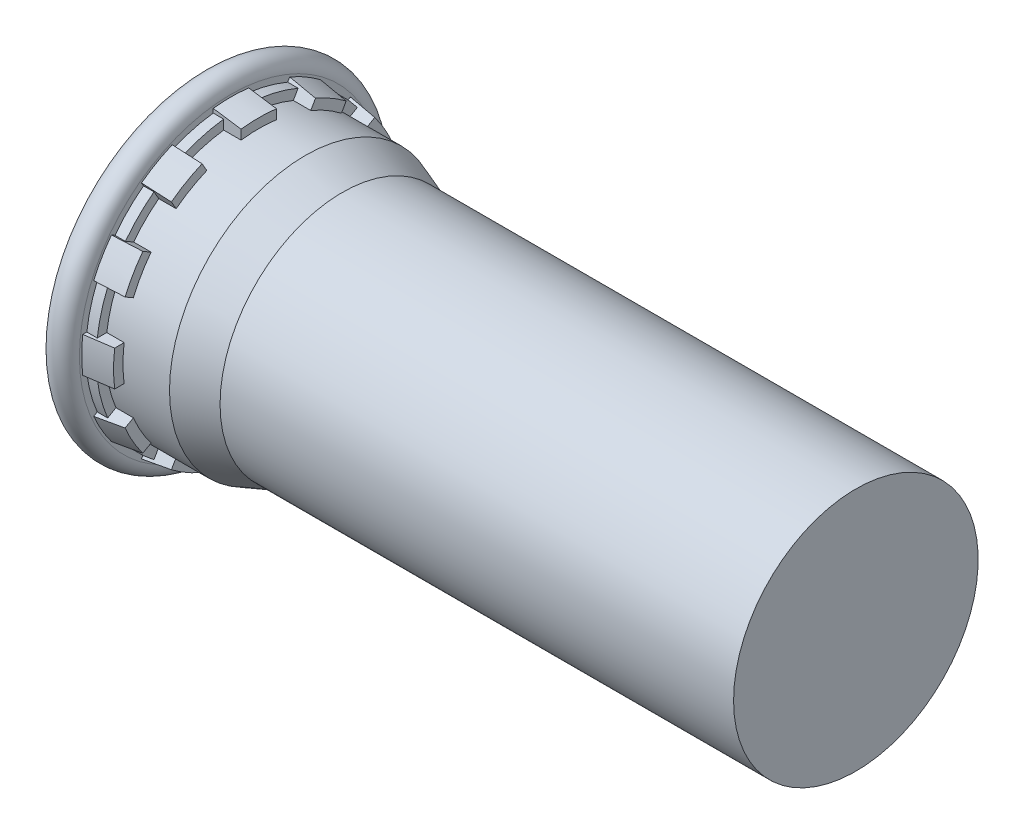
SolidWorks part; units mm, degrees
revolve "BaseBody" add sketch "BodySke" angle 360 about L6
sketch "BodySke" plane through (0, 0, 0) normal (0, 0, 1) x (1, 0, 0)
  line L0 (0, 0) -> (0, 4.4171)
  line L1 (0.8128, 4.4221) -> (0.8128, 4.3561)
  line L2 (0.8128, 4.3561) -> (1.6256, 4.238)
  line L3 (4.064, 3.5687) -> (19.05, 3.5687)
  line L4 (19.05, 3.5687) -> (19.05, 0)
  line L5 (19.05, 0) -> (0, 0)
  line L6 (0, 0) -> (50.554, 0) construction
  line L7 (1.6256, 4.238) -> (1.6256, 3.9624)
  line L8 (2.9823, 3.9624) -> (1.6256, 3.9624)
  line L9 (-9.525, 4.826) -> (9.525, 4.826) construction
  line L11 (4.064, 3.5687) -> (2.9823, 3.9624)
  line L13 (9.525, -4.826) -> (-9.525, -4.826) construction
  line L14 (0.0051, 4.4221) -> (0.0051, 4.4171)
  line L15 (0, 4.4171) -> (0.0051, 4.4171)
  arc A0 (0.0051, 4.4221) -> (0.8128, 4.4221) centre (0.4089, 4.4221) cw
  dimension "Length" = 19.05
  dimension "H_dia" = 9.652
  dimension "Shoulder_lower_dia" = 8.7122
  dimension "Shoulder_upper_dia" = 8.476
  dimension "D1" = 0.0051
  dimension "D2" = 0.0051
  dimension "Shoulder_ht" = 1.6256
  dimension "T_dim" = 0.8128
  dimension "Diameter" = 7.1374
  dimension "Neck_dia" = 7.9248
  dimension "Neck_len" = 4.064
  dimension "D3" = 20
cosmetic thread "ThreadCosmetic" [suppressed] parameters "Thread_length"=15.621, "Thread_minor"=4.8387
extrude "RibCut1" cut sketch "RibCut1Ske" against normal blind 0.508
sketch "RibCut1Ske" plane through (1.6256, 0, 0) normal (1, 0, 0) x (0, 0, -1)
  line L0 (0.5172, 3.9285) -> (0.5172, 4.7982)
  line L1 (1.5163, 3.6608) -> (1.9512, 4.414)
  line L2 (0, 0) -> (0, 4.9784) construction
  line L3 (0, 0) -> (0.5172, 3.9285) construction
  line L4 (0, 0) -> (1.5163, 3.6608) construction
  arc A1 (1.5163, 3.6608) -> (0.5172, 3.9285) centre (0, 0) ccw
  arc A2 (1.9512, 4.414) -> (0.5172, 4.7982) centre (0, 0) ccw
  dimension "Angle" = 30
  dimension "Inner_dia" = 7.9248
  dimension "Outer_dia" = 9.652
  dimension "Rib_root_half_angle" = 7.5
  dimension "Rib_root_gap_angle" = 15
ref_plane "Plane1" through (0, 0, 0) normal (0, 0, 1) x (1, 0, 0)
ref_plane "Plane2" through (0, 0, 0) normal (0, 1, 0) x (1, 0, 0)
ref_plane "Plane3" through (0, 0, 0) normal (1, 0, 0) x (0, 0, -1)
sketch "RibCut2Ske" plane through (1.6256, 0, 0) normal (1, 0, 0) x (0, 0, -1)
  line L0 (0.5172, 4.2063) -> (0.5172, 4.7982)
  line L1 (1.6553, 3.9014) -> (1.9512, 4.414)
  line L2 (0.5172, 3.9285) -> (0.5172, 5.7403) construction
  line L3 (0, 0) -> (0, 5.0239) construction
  line L4 (0, 0) -> (0.5172, 3.9285) construction
  line L5 (0, 0) -> (1.5163, 3.6608) construction
  line L6 (1.5163, 3.6608) -> (2.4258, 5.2359) construction
  arc A1 (1.6553, 3.9014) -> (0.5172, 4.2063) centre (0, 0) ccw
  arc A2 (1.9512, 4.414) -> (0.5172, 4.7982) centre (0, 0) ccw
  circle A4 centre (0, 0) radius 3.9624 construction
  dimension "Angle" = 30
  dimension "Outer_dia" = 9.652
  dimension "Rib_root_half_angle" = 7.5
  dimension "Rib_root_gap_angle" = 15
extrude "RibCut2" cut sketch "RibCut2Ske" against normal blind 0.8128
pattern_circular "RibCutsPat" count 12 every 30 about axis through (0, 0, 0) along (1, 0, 0) of "RibCut2", "RibCut1"
equation "' \"Diameter@BodySke\" = 0.281"
equation "' \"Length@BodySke\" = 0.75"
equation "' \"Neck_dia@BodySke\" = 0.312"
equation "' \"H_dia@BodySke\" = 0.38"
equation "' \"Neck_len@BodySke\" = 0.16"
equation "\"T_dim@BodySke\" = \"Neck_len@BodySke\" * 0.2"
equation "\"Shoulder_ht@BodySke\" = \"Neck_len@BodySke\" * 0.4"
equation "\"Shoulder_lower_dia@BodySke\" = \"H_dia@BodySke\" - \"Neck_len@BodySke\" * 0.2 - .005"
equation "\"Shoulder_upper_dia@BodySke\" = ( \"Shoulder_lower_dia@BodySke\" + \"Diameter@BodySke\" ) /2"
equation "\"Shoulder_upper_dia@BodySke\" = \"Diameter@BodySke\" +  ( \"Shoulder_lower_dia@BodySke\" - \"Diameter@BodySke\" ) * 0.85"
equation "\"Num_ribs@RibCutsPat\" = 12"
equation "\"Angle@RibCutsPat\" = 360 / \"Num_ribs@RibCutsPat\""
equation "\"Angle@RibCut1Ske\" =\"Angle@RibCutsPat\""
equation "\"Rib_root_half_angle@RibCut1Ske\" = \"Angle@RibCut1Ske\" / 4"
equation "\"Rib_root_gap_angle@RibCut1Ske\" = \"Angle@RibCut1Ske\" - (2 * \"Rib_root_half_angle@RibCut1Ske\" )"
equation "\"Inner_dia@RibCut1Ske\" = \"Neck_dia@BodySke\""
equation "\"Outer_dia@RibCut1Ske\" = \"H_dia@BodySke\""
equation "\"Depth@RibCut1\" =  \"Neck_len@BodySke\" * 0.125"
equation "\"Angle@RibCut2Ske\" =\"Angle@RibCutsPat\""
equation "\"Rib_root_half_angle@RibCut2Ske\" = \"Angle@RibCut1Ske\" / 4"
equation "\"Rib_root_gap_angle@RibCut2Ske\" = \"Angle@RibCut1Ske\" - (2 * \"Rib_root_half_angle@RibCut1Ske\" )"
equation "\"Rib_root_dia@RibCut2Ske\" = \"Neck_dia@BodySke\""
equation "\"Inner_dia@RibCut2Ske\" = \"Shoulder_upper_dia@BodySke\""
equation "\"Outer_dia@RibCut2Ske\" = \"H_dia@BodySke\""
equation "\"Depth@RibCut2\" =  \"Neck_len@BodySke\" * 0.2"
